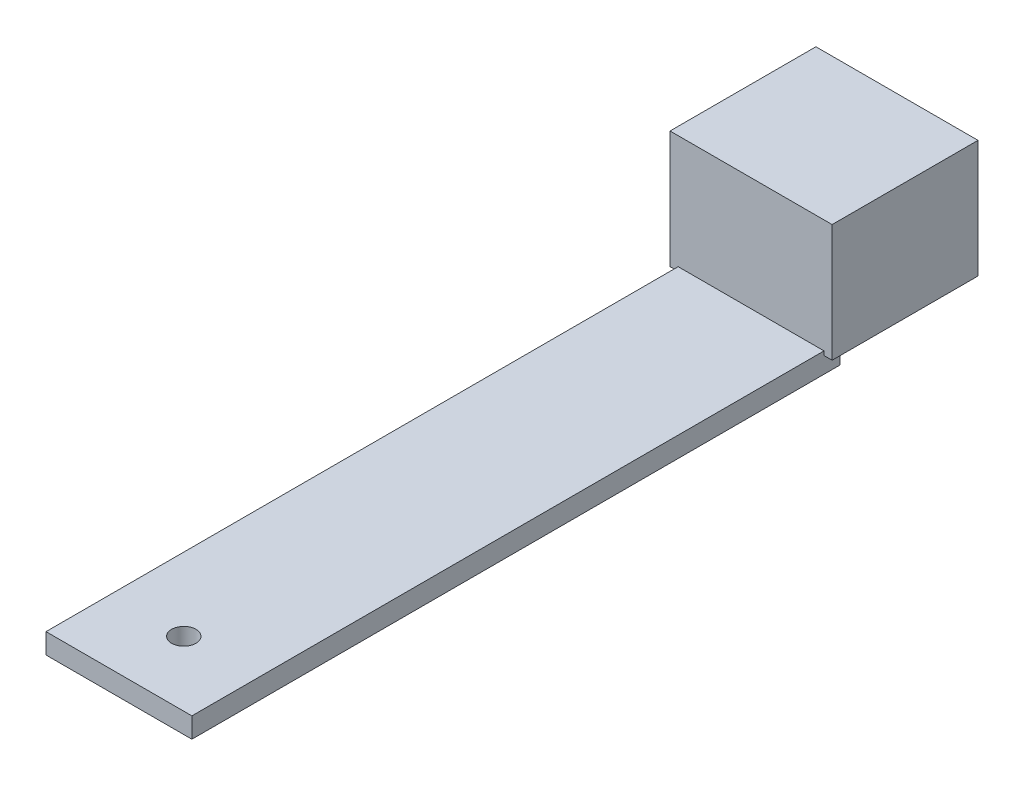
SolidWorks part; units mm, degrees
ref_plane "Front Plane" through (0, 0, 0) normal (0, 0, 1) x (1, 0, 0)
ref_plane "Top Plane" through (0, 0, 0) normal (0, 1, 0) x (1, 0, 0)
ref_plane "Right Plane" through (0, 0, 0) normal (1, 0, 0) x (0, 0, -1)
ref_plane "PZ_m72_000" through (0, 0, -72) normal (0, 0, 1) x (1, 0, 0)
sketch "S_box1" plane through (0, 0, -72) normal (0, 0, 1) x (1, 0, 0)
  line L0 (-9, -20.7) -> (9, -20.7)
  line L1 (9, -20.7) -> (9, -18.2)
  line L2 (9, -18.2) -> (-9, -18.2)
  line L3 (-9, -18.2) -> (-9, -20.7)
  dimension "P1" = 9
  dimension "P2" = 20.7
  dimension "P3" = 9
  dimension "P4" = 20.7
  dimension "P5" = 9
  dimension "P6" = 18.2
  dimension "P7" = 9
  dimension "P8" = 18.2
extrude "Boss_1" add sketch "S_box1" along normal blind 80
ref_plane "PZ_m88_000" through (0, 0, -88) normal (0, 0, 1) x (1, 0, 0)
sketch "S_box2" plane through (0, 0, -88) normal (0, 0, 1) x (1, 0, 0)
  line L0 (-10, -18.7) -> (10, -18.7)
  line L1 (10, -18.7) -> (10, -4.2)
  line L2 (10, -4.2) -> (-10, -4.2)
  line L3 (-10, -4.2) -> (-10, -18.7)
  dimension "P1" = 10
  dimension "P2" = 18.7
  dimension "P3" = 10
  dimension "P4" = 18.7
  dimension "P5" = 10
  dimension "P6" = 4.2
  dimension "P7" = 10
  dimension "P8" = 4.2
extrude "Boss_2" add sketch "S_box2" along normal blind 18
ref_plane "PY_m20_800" through (0, -20.8, 0) normal (0, 1, 0) x (1, 0, 0)
sketch "S_hole3" plane through (0, -20.8, 0) normal (0, 1, 0) x (1, 0, 0)
  circle A0 centre (0, 0) radius 1.5
  dimension "D1_S_hole3" = 3
extrude "Hole_3" cut sketch "S_hole3" along normal blind 2.7
equation "\"plate_t\" = 3"
equation "\"clearance\" = 0.4"
